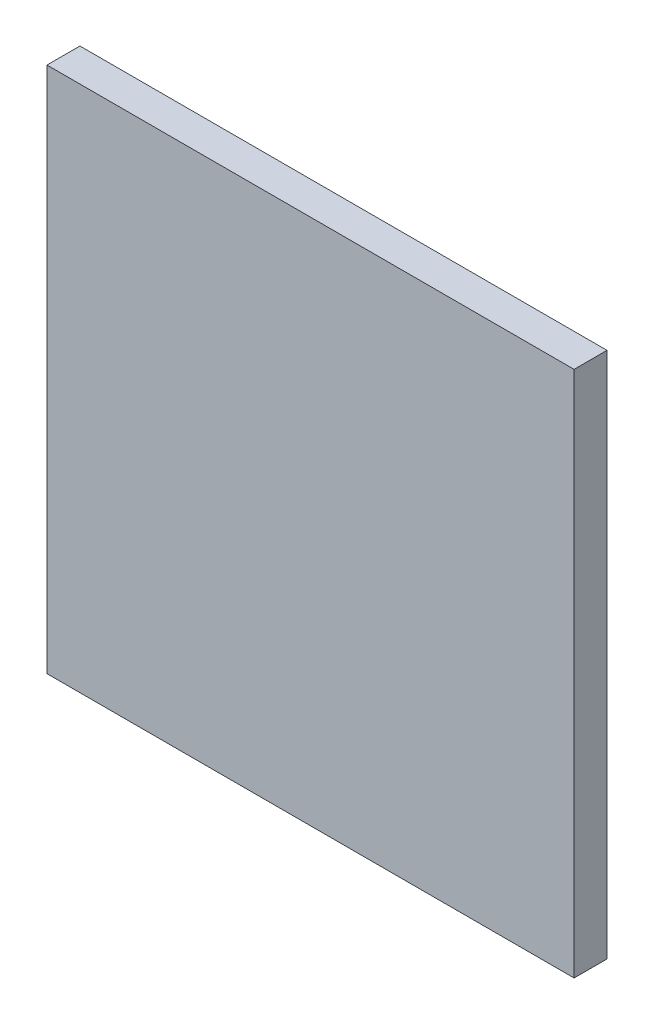
SolidWorks part; units mm, degrees
ref_plane "Front Plane" through (0, 0, 0) normal (0, 0, 1) x (1, 0, 0)
ref_plane "Top Plane" through (0, 0, 0) normal (0, 1, 0) x (1, 0, 0)
ref_plane "Right Plane" through (0, 0, 0) normal (1, 0, 0) x (0, 0, -1)
sketch "Sketch2" plane through (0, 0, 0) normal (0, 0, 1) x (1, 0, 0)
  line L1 (0, 0) -> (101.6, 0)
  line L2 (0, 0) -> (0, 101.6)
  line L3 (0, 101.6) -> (101.6, 101.6)
  line L4 (101.6, 0) -> (101.6, 101.6)
  dimension "D1" = 101.6
  dimension "D2" = 101.6
extrude "Extrude1" add sketch "Sketch2" along normal blind 6.35
